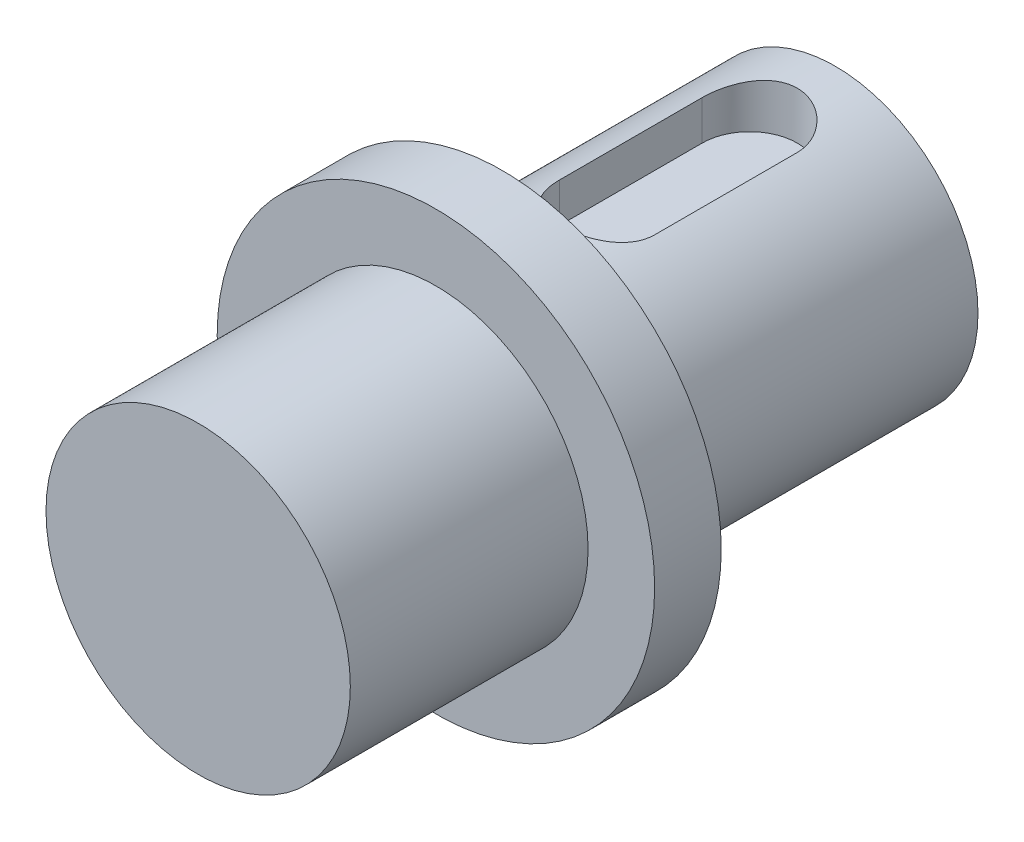
SolidWorks part; units mm, degrees
ref_plane "Front Plane" through (0, 0, 0) normal (0, 0, 1) x (1, 0, 0)
ref_plane "Top Plane" through (0, 0, 0) normal (0, 1, 0) x (1, 0, 0)
ref_plane "Right Plane" through (0, 0, 0) normal (1, 0, 0) x (0, 0, -1)
sketch "Sketch1" plane through (0, 0, 0) normal (0, 0, 1) x (1, 0, 0)
  circle A0 centre (0, 0) radius 15
extrude "Boss-Extrude1" add sketch "Sketch1" along normal blind 35
sketch "Sketch2" plane through (0, 0, 35) normal (0, 0, 1) x (1, 0, 0)
  circle A0 centre (0, 0) radius 23
extrude "Boss-Extrude2" add sketch "Sketch2" along normal blind 7
sketch "Sketch3" plane through (0, 0, 42) normal (0, 0, 1) x (1, 0, 0)
  circle A0 centre (0, 0) radius 16
extrude "Boss-Extrude3" add sketch "Sketch3" along normal blind 25
ref_plane "Plane1" through (0, 10, 0) normal (0, 1, 0) x (1, 0, 0)
sketch "Sketch4" plane through (0, 10, 0) normal (0, 1, 0) x (1, 0, 0)
  line L0 (0, 0) -> (0, -35) construction
  line L1 (15, -35) -> (-15, -35) construction
  line L2 (15, 0) -> (-15, 0) construction
  line L3 (5, -24) -> (5, -9)
  line L4 (-5, -9) -> (-5, -24)
  arc A0 (5, -9) -> (-5, -9) centre (0, -9) ccw
  arc A1 (-5, -24) -> (5, -24) centre (0, -24) ccw
  dimension "D1" = 9
  dimension "D2" = 15
extrude "Cut-Extrude1" cut sketch "Sketch4" along normal blind 25
